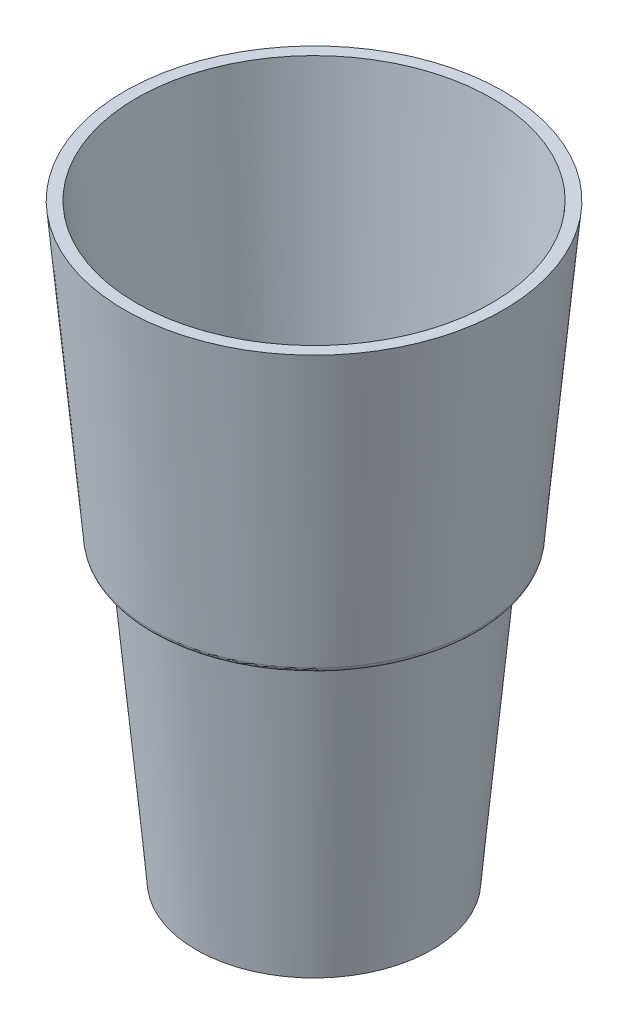
SolidWorks part; units mm, degrees
ref_plane "Front Plane" through (0, 0, 0) normal (0, 0, 1) x (1, 0, 0)
ref_plane "Top Plane" through (0, 0, 0) normal (0, 1, 0) x (1, 0, 0)
ref_plane "Right Plane" through (0, 0, 0) normal (1, 0, 0) x (0, 0, -1)
sketch "Sketch1" plane through (0, 0, 0) normal (0, 0, 1) x (1, 0, 0)
  line L0 (0, 0) -> (25.4, 0)
  line L1 (25.4, 0) -> (31.1859, 63.5)
  line L2 (31.1859, 63.5) -> (34.9959, 63.5)
  line L3 (34.9959, 63.5) -> (40.7818, 127)
  line L4 (40.7818, 127) -> (0, 127)
  line L6 (0, 0) -> (0, 127)
  dimension "D1" = 25.4
  dimension "D2" = 63.5
  dimension "D3" = 63.5
  dimension "D4" = 3.81
revolve "Revolve2" add sketch "Sketch1" angle 360 about L6
fillet "Fillet1" radius 1.27 2 edges at (0, 63.5, -34.9959) (0, 63.5, -31.1859)
shell "Shell1" thickness 2.54
